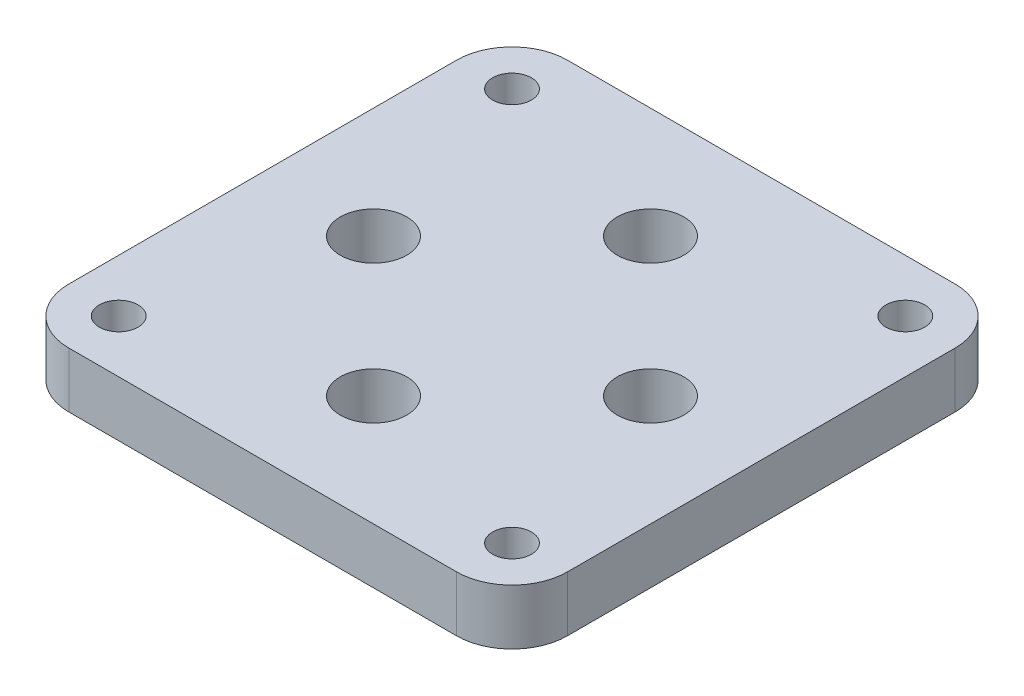
SolidWorks part; units mm, degrees
ref_plane "Front Plane" through (0, 0, 0) normal (0, 0, 1) x (1, 0, 0)
ref_plane "Top Plane" through (0, 0, 0) normal (0, 1, 0) x (1, 0, 0)
ref_plane "Right Plane" through (0, 0, 0) normal (1, 0, 0) x (0, 0, -1)
sketch "Sketch1" plane through (0, 0, 0) normal (0, 1, 0) x (1, 0, 0)
  line L1 (-45, 45) -> (45, 45)
  line L2 (-45, 45) -> (-45, -45)
  line L3 (-45, -45) -> (45, -45)
  line L4 (45, 45) -> (45, -45)
  line L5 (-45, 45) -> (45, -45) construction
  line L6 (-45, -45) -> (45, 45) construction
  point P0 (0, 0)
  dimension "D1" = 90
  dimension "D2" = 90
extrude "Boss-Extrude1" add sketch "Sketch1" along normal blind 10
sketch "Sketch2" plane through (0, 10, 0) normal (0, 1, 0) x (1, 0, 0)
  line L0 (-45, 45) -> (-45, -45) construction
  line L1 (45, 45) -> (-45, 45) construction
  line L2 (45, -45) -> (45, 45) construction
  line L3 (-45, -45) -> (45, -45) construction
  circle A0 centre (-35.5, 35.5) radius 3
  circle A1 centre (35.5, -35.5) radius 3
  circle A2 centre (35.5, 35.5) radius 3
  circle A3 centre (-35.5, -35.5) radius 3
  dimension "D1" = 6
  dimension "D5" = 6
  dimension "D7" = 6
  dimension "D8" = 6
  dimension "D2" = 9.5
  dimension "D3" = 9.5
  dimension "D4" = 9.5
  dimension "D6" = 9.5
  dimension "D9" = 9.5
  dimension "D10" = 9.5
  dimension "D11" = 9.5
  dimension "D12" = 9.5
sketch "Sketch3" plane through (0, 10, 0) normal (0, 1, 0) x (1, 0, 0)
  circle A1 centre (0, 25) radius 6
  circle A2 centre (-25, 0) radius 6
  circle A3 centre (0, -25) radius 6
  circle A4 centre (25, 0) radius 6
  dimension "D2" = 12
  dimension "D3" = 12
  dimension "D4" = 12
  dimension "D5" = 12
hole_wizard "M6 Clearance Hole2" positions "3DSketch3" profile "Sketch6" hole size "M6" standard "ISO" end condition through all
sketch3d "3DSketch3"
  point P0 (-35.5, 10, -35.5)
  point P3 (35.5, 10, -35.5)
  point P6 (-35.5, 10, 35.5)
  point P9 (35.5, 10, 35.5)
sketch "Sketch6" plane through (-35.5, 10, -35.5) normal (1, 0, 0) x (0, 0, 1)
  line L0 (0, 0) -> (0, 10)
  line L1 (0, 10) -> (3.5, 10)
  line L2 (3.5, 10) -> (3.5, 0)
  line L5 (3.5, 0) -> (0, 0)
  line L11 (0, -6.35) -> (0, 107.95) construction
  dimension "Thru Hole Dia." = 7
  dimension "Thru Hole Depth" = 10
extrude "Cut-Extrude2" cut sketch "Sketch3" against normal blind 26 contours A3 | A4 | A2 | A1
fillet "Fillet1" radius 10 4 edges at (45, 5, -45) (-45, 5, -45) (45, 5, 45) (-45, 5, 45)
